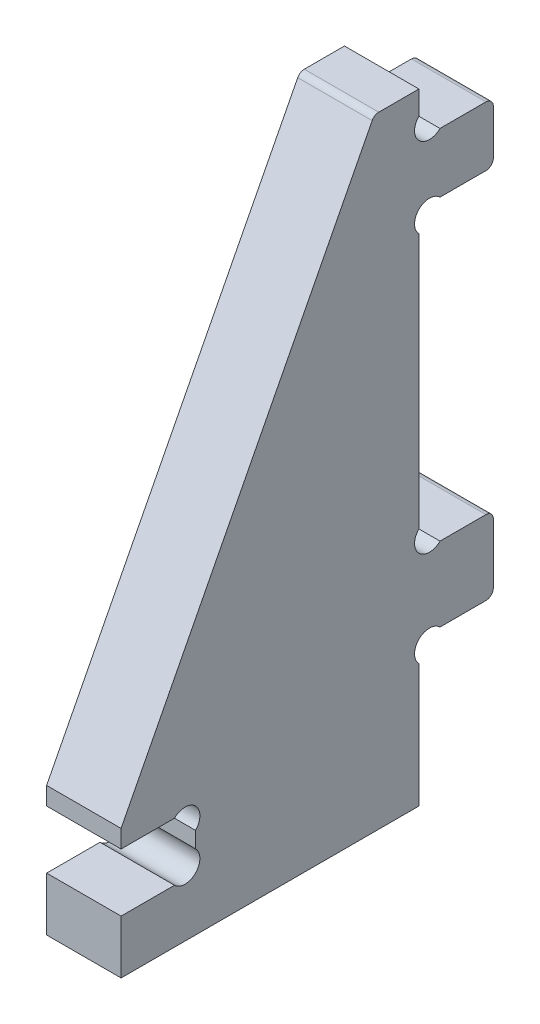
SolidWorks part; units mm, degrees
ref_plane "정면" through (0, 0, 0) normal (0, 0, 1) x (1, 0, 0)
ref_plane "윗면" through (0, 0, 0) normal (0, 1, 0) x (1, 0, 0)
ref_plane "우측면" through (0, 0, 0) normal (1, 0, 0) x (0, 0, -1)
sketch "스케치1" plane through (0, 0, 0) normal (1, 0, 0) x (0, 0, -1)
  line L0 (0, 0) -> (0, 12)
  line L1 (0, 12) -> (17, 45)
  line L2 (17, 45) -> (20, 45)
  line L3 (20, 45) -> (20, 0)
  line L4 (20, 0) -> (0, 0)
  dimension "D1" = 45
  dimension "D2" = 20
  dimension "D3" = 3
  dimension "D4" = 12
extrude "보스-돌출1" add sketch "스케치1" along normal blind 5
sketch "스케치7" plane through (5, 0, 0) normal (1, 0, 0) x (0, 0, -1)
  line L1 (0, 0) -> (5, 0)
  line L2 (0, 0) -> (0, 10.8)
  line L3 (0, 10.8) -> (5, 10.8)
  line L4 (5, 0) -> (5, 10.8)
  dimension "D1" = 5
extrude "컷-돌출1" cut sketch "스케치7" against normal blind 5
sketch "스케치8" plane through (5, 0, 0) normal (1, 0, 0) x (0, 0, -1)
  line L1 (20, 0) -> (20, 45) construction
  line L2 (20, 3.3) -> (5, 3.3)
  line L3 (20, 3.3) -> (20, 0)
  line L4 (20, 0) -> (5, 0)
  line L5 (5, 3.3) -> (5, 0)
  dimension "D1" = 3.3
extrude "컷-돌출2" cut sketch "스케치8" against normal blind 5
sketch "스케치10" plane through (5, 0, 0) normal (1, 0, 0) x (0, 0, -1)
  line L1 (0, 5.8) -> (0, -4.2) construction
  line L2 (5, 3.3) -> (0, 3.3)
  line L3 (5, 3.3) -> (5, 6.9)
  line L4 (5, 6.9) -> (0, 6.9)
  line L6 (0, 3.3) -> (0, 6.9)
  dimension "D1" = 3.6
extrude "보스-돌출2" add sketch "스케치10" against normal blind 5
sketch "스케치9" plane through (5, 0, 0) normal (1, 0, 0) x (0, 0, -1)
  line L2 (5, 10.8) -> (4.2929, 10.0929) construction
  line L4 (5, 10.8) -> (0, 10.8) construction
  line L6 (5, 6.9) -> (4.2929, 7.6071) construction
  line L7 (5, 6.9) -> (0, 6.9) construction
  circle A1 centre (4.2929, 10.0929) radius 1
  circle A2 centre (4.2929, 7.6071) radius 1
  dimension "D1" = 2
  dimension "D2" = 45
  dimension "D4" = 45
extrude "컷-돌출3" cut sketch "스케치9" against normal blind 5
sketch "스케치11" plane through (5, 0, 0) normal (1, 0, 0) x (0, 0, -1)
  line L0 (20, 3.3) -> (20, 45) construction
  line L1 (20, 18) -> (25, 18)
  line L2 (20, 18) -> (20, 13)
  line L3 (20, 13) -> (25, 13)
  line L4 (25, 18) -> (25, 13)
  line L5 (25, 8.1077) -> (25, 23.8923) construction
  line L6 (25, 30) -> (25, 45) construction
  line L7 (20, 42) -> (25, 42)
  line L8 (20, 42) -> (20, 38)
  line L9 (20, 38) -> (25, 38)
  line L10 (25, 42) -> (25, 38)
  line L11 (20, 45) -> (17, 45) construction
  dimension "D1" = 3
  dimension "D2" = 4
  dimension "D3" = 20
  dimension "D4" = 5
sketch "스케치15" plane through (5, 0, 0) normal (1, 0, 0) x (0, 0, -1)
  line L1 (20, 3.3) -> (20, 45) construction
  line L2 (20, 38) -> (25, 38)
  line L3 (20, 38) -> (20, 42)
  line L4 (20, 42) -> (25, 42)
  line L7 (25, 38) -> (25, 42)
  line L8 (25, 30) -> (25, 45) construction
  line L9 (25, 8.1077) -> (25, 23.8923) construction
  line L10 (20, 13) -> (25, 13)
  line L11 (20, 13) -> (20, 18)
  line L12 (20, 18) -> (25, 18)
  line L13 (25, 13) -> (25, 18)
  line L14 (20, 45) -> (17, 45) construction
  dimension "D1" = 3
  dimension "D2" = 4
  dimension "D3" = 20
  dimension "D4" = 5
extrude "보스-돌출6" add sketch "스케치15" against normal blind 5
extrude "보스-돌출3" add sketch "스케치11" against normal blind 5
sketch "스케치12" plane through (5, 0, 0) normal (1, 0, 0) x (0, 0, -1)
  line L0 (20.7071, 42.7071) -> (20, 42) construction
  line L1 (20.7071, 37.2929) -> (20, 38) construction
  line L2 (20.7071, 12.2929) -> (20, 13) construction
  line L3 (20, 18) -> (20.7071, 18.7071) construction
  circle A0 centre (20.7071, 18.7071) radius 1
  circle A1 centre (20.7071, 12.2929) radius 1
  circle A2 centre (20.7071, 37.2929) radius 1
  circle A3 centre (20.7071, 42.7071) radius 1
  dimension "D5" = 2
extrude "컷-돌출4" cut sketch "스케치12" against normal blind 5
fillet "필렛1" radius 0.5 5 edges at (2.5, 13, -25) (2.5, 38, -25) (2.5, 18, -25) (2.5, 42, -25) (2.5, 45, -17)
